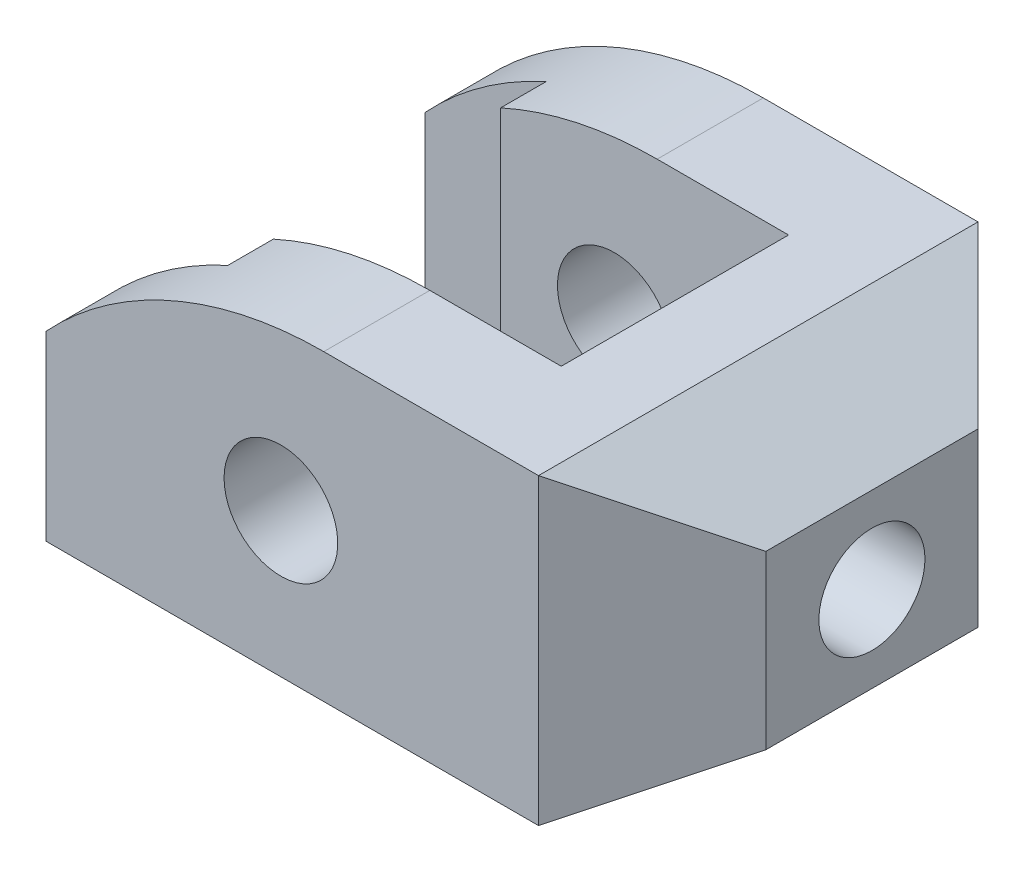
SolidWorks part; units mm, degrees
material "1060 Alloy"
ref_plane "Front Plane" through (0, 0, 0) normal (0, 0, 1) x (1, 0, 0)
ref_plane "Top Plane" through (0, 0, 0) normal (0, 1, 0) x (1, 0, 0)
ref_plane "Right Plane" through (0, 0, 0) normal (1, 0, 0) x (0, 0, -1)
sketch "Sketch1" plane through (0, 0, 0) normal (0, 0, 1) x (1, 0, 0)
  line L0 (0, 0) -> (0, 24)
  line L1 (0, 0) -> (65, 0)
  line L2 (65, 0) -> (80, 8.6603)
  line L3 (80, 8.6603) -> (80, 31.3397)
  line L4 (80, 31.3397) -> (65, 40)
  line L5 (65, 40) -> (36.6606, 40)
  arc A0 (36.6606, 40) -> (0, 24) centre (36.6606, -10) ccw
  circle A1 centre (31, 19) radius 7.5
  dimension "D1" = 24
  dimension "D8" = 50
  dimension "D9" = 19
  dimension "D10" = 31
  dimension "D11" = 15
  dimension "D2" = 65
  dimension "D3" = 15
  dimension "D4" = 30
  dimension "D5" = 40
  dimension "D6" = 30
  dimension "D7" = 15
extrude "Boss-Extrude1" add sketch "Sketch1" along normal blind 58
sketch "Sketch2" plane through (0, 40, 0) normal (0, 1, 0) x (1, 0, 0)
  line L0 (0, -58) -> (0, 0) construction
  line L1 (0, -8) -> (16, -8)
  line L2 (0, -8) -> (0, -50)
  line L3 (0, -50) -> (16, -50)
  line L4 (16, -8) -> (16, -14)
  line L5 (16, -44) -> (16, -50)
  line L6 (16, -14) -> (54, -14)
  line L8 (16, -44) -> (54, -44)
  line L9 (54, -14) -> (54, -44)
  line L10 (36.6606, 0) -> (0, 0) construction
  line L11 (0, -58) -> (36.6606, -58) construction
  dimension "D1" = 8
  dimension "D2" = 8
  dimension "D3" = 14
  dimension "D4" = 14
  dimension "D5" = 16
  dimension "D6" = 11
extrude "Cut-Extrude1" cut sketch "Sketch2" against normal through all
sketch "Sketch5" plane through (0, 40, 0) normal (0, 1, 0) x (1, 0, 0)
  line L0 (65, 0) -> (80, -15)
  line L1 (80, -58) -> (80, 0) construction
  line L2 (80, -15) -> (80, 0)
  line L3 (80, 0) -> (65, 0)
  line L4 (65, -58) -> (80, -58)
  line L5 (80, -58) -> (80, -43)
  line L6 (80, -43) -> (65, -58)
  dimension "D1" = 45
  dimension "D2" = 45
extrude "Cut-Extrude6" cut sketch "Sketch5" against normal through all
sketch "Sketch6" plane through (80, 0, 0) normal (1, 0, 0) x (0, 0, -1)
  line L0 (-43, 31.3397) -> (-15, 31.3397) construction
  line L1 (-43, 8.6603) -> (-43, 31.3397) construction
  circle A0 centre (-29, 20) radius 7
  dimension "D1" = 14
  dimension "D2" = 11.3397
  dimension "D3" = 14
extrude "Cut-Extrude7" cut sketch "Sketch6" against normal through all
equation "\"a\"= 58"
equation "\"b\"= 40"
equation "\"c\"= 65"
